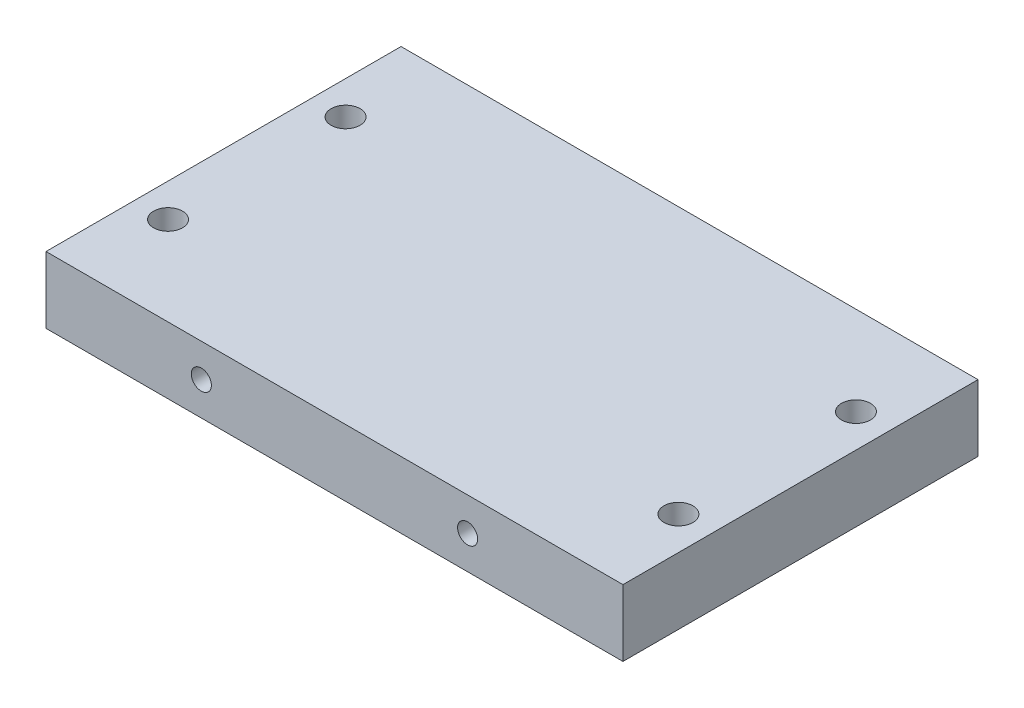
SolidWorks part; units mm, degrees
material "6061 Alloy"
ref_plane "Front Plane" through (0, 0, 0) normal (0, 0, 1) x (1, 0, 0)
ref_plane "Top Plane" through (0, 0, 0) normal (0, 1, 0) x (1, 0, 0)
ref_plane "Right Plane" through (0, 0, 0) normal (1, 0, 0) x (0, 0, -1)
sketch "Sketch1" plane through (0, 0, 0) normal (0, 1, 0) x (1, 0, 0)
  line L1 (32.5, -20) -> (-32.5, -20)
  line L2 (32.5, -20) -> (32.5, 20)
  line L3 (32.5, 20) -> (-32.5, 20)
  line L4 (-32.5, -20) -> (-32.5, 20)
  line L5 (32.5, -20) -> (-32.5, 20) construction
  line L6 (32.5, 20) -> (-32.5, -20) construction
  point P0 (0, 0)
  dimension "D1" = 40
  dimension "D2" = 65
extrude "Boss-Extrude1" add sketch "Sketch1" along normal blind 7.5
sketch "Sketch2" plane through (0, 0, 20) normal (0, 0, 1) x (1, 0, 0)
  line L0 (0, 0) -> (0, 7.5)
  line L1 (-32.5, 0) -> (32.5, 0) construction
  line L2 (-32.5, 7.5) -> (32.5, 7.5) construction
  line L3 (15, 3.75) -> (-15, 3.75)
  point P9 (0, 3.75)
  dimension "D1" = 30
hole_wizard "#4-40 Tapped Hole1" positions "Sketch3" profile "Sketch4" tap size "#4-40" standard "ANSI Inch"
sketch "Sketch3" plane through (0, 0, 20) normal (0, 0, 1) x (1, 0, 0)
  point P0 (-15, 3.75)
  point P3 (15, 3.75)
sketch "Sketch4" plane through (-15, 3.75, 20) normal (1, 0, 0) x (0, -1, 0)
  line L0 (0, 0) -> (0, 8.2792)
  line L1 (0, 8.2792) -> (1.1303, 7.6)
  line L2 (1.1303, 7.6) -> (1.1303, 0)
  line L5 (1.1303, 0) -> (0, 0)
  line L10 (0, 8.2792) -> (-1.1303, 7.6) construction
  line L11 (0, -6.35) -> (0, 107.95) construction
  dimension "Tap Drill Dia." = 2.2606
  dimension "Tap Drill Depth" = 7.6
  dimension "Drill Angle" = 118
cosmetic thread "Hole Thread1" parameters "D1"=5.69, "D2"=2.8448
cosmetic thread "Hole Thread2" parameters "D1"=5.69, "D2"=2.8448
hole_wizard "#4-40 Tapped Hole2" positions "Sketch5" profile "Sketch6" tap size "#4-40" standard "ANSI Inch"
sketch "Sketch5" plane through (0, 0, -20) normal (0, 0, -1) x (-1, 0, 0)
  point P0 (-15, 3.75)
  point P3 (15, 3.75)
sketch "Sketch6" plane through (15, 3.75, -20) normal (1, 0, 0) x (0, 1, 0)
  line L0 (0, 0) -> (0, 8.2792)
  line L1 (0, 8.2792) -> (1.1303, 7.6)
  line L2 (1.1303, 7.6) -> (1.1303, 0)
  line L5 (1.1303, 0) -> (0, 0)
  line L10 (0, 8.2792) -> (-1.1303, 7.6) construction
  line L11 (0, -6.35) -> (0, 107.95) construction
  dimension "Tap Drill Dia." = 2.2606
  dimension "Tap Drill Depth" = 7.6
  dimension "Drill Angle" = 118
cosmetic thread "Hole Thread3" parameters "D1"=5.69, "D2"=2.8448
cosmetic thread "Hole Thread4" parameters "D1"=5.69, "D2"=2.8448
sketch "Sketch7" plane through (0, 7.5, 0) normal (0, 1, 0) x (1, 0, 0)
  line L1 (28.75, -10) -> (-28.75, -10)
  line L2 (28.75, -10) -> (28.75, 10)
  line L3 (28.75, 10) -> (-28.75, 10)
  line L4 (-28.75, -10) -> (-28.75, 10)
  line L5 (28.75, -10) -> (-28.75, 10) construction
  line L6 (28.75, 10) -> (-28.75, -10) construction
  point P0 (0, 0)
  dimension "D1" = 57.5
  dimension "D2" = 20
hole_wizard "CBORE for #4 Socket Head Cap Screw1" positions "Sketch10" profile "Sketch11" counterbore size "#4" standard "ANSI Inch" end condition through all
sketch "Sketch10" plane through (0, 0, 0) normal (0, -1, 0) x (-1, 0, 0)
  point P0 (-28.75, -10)
  point P3 (-28.75, 10)
  point P6 (28.75, 10)
  point P9 (28.75, -10)
sketch "Sketch11" plane through (28.75, 0, 10) normal (1, 0, 0) x (0, 0, -1)
  line L0 (0, 0) -> (0, 7.5)
  line L1 (0, 7.5) -> (1.6319, 7.5)
  line L3 (1.6319, 7.5) -> (1.6319, 2.8448)
  line L4 (1.6319, 2.8448) -> (2.7788, 2.8448)
  line L5 (2.7788, 2.8448) -> (2.7788, 0)
  line L7 (2.7788, 0) -> (0, 0)
  line L11 (0, -6.35) -> (0, 107.95) construction
  dimension "Thru Hole Dia." = 3.2639
  dimension "Thru Hole Depth" = 7.5
  dimension "C'Bore Dia." = 5.5575
  dimension "C'Bore Depth" = 2.8448
